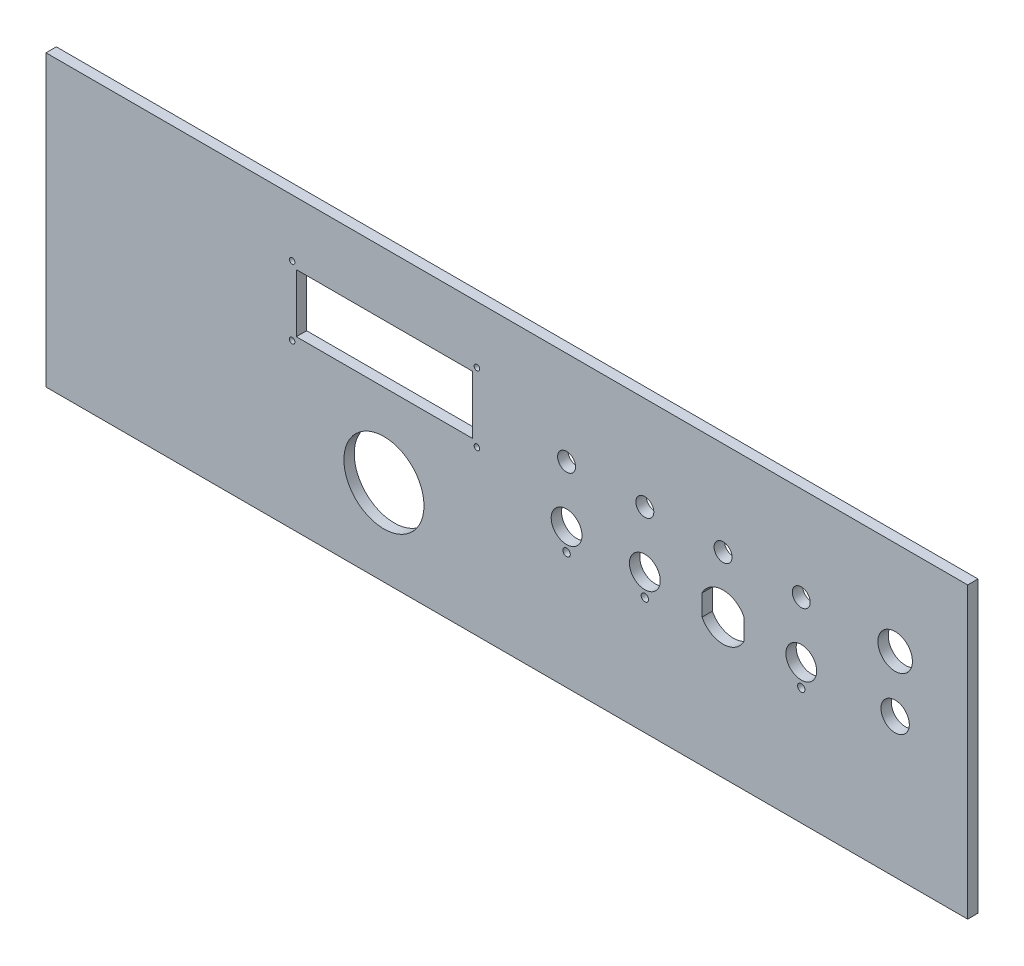
SolidWorks part; units mm, degrees
ref_plane "Front Plane" through (0, 0, 0) normal (0, 0, 1) x (1, 0, 0)
ref_plane "Top Plane" through (0, 0, 0) normal (0, 1, 0) x (1, 0, 0)
ref_plane "Right Plane" through (0, 0, 0) normal (1, 0, 0) x (0, 0, -1)
sketch "Sketch2" plane through (0, 0, 0) normal (0, 0, 1) x (1, 0, 0)
  line L1 (0, 0) -> (374.0912, 0)
  line L2 (0, 0) -> (0, 117.5004)
  line L3 (0, 117.5004) -> (374.0912, 117.5004)
  line L4 (374.0912, 0) -> (374.0912, 117.5004)
  line L5 (101.6, 92.1004) -> (173.2, 92.1004)
  line L6 (101.6, 92.1004) -> (101.6, 68.5004)
  line L7 (101.6, 68.5004) -> (173.2, 68.5004)
  line L8 (173.2, 92.1004) -> (173.2, 68.5004)
  circle A0 centre (137.16, 34.9504) radius 16.25
  dimension "D7" = 32.5
  dimension "D1" = 117.5004
  dimension "D2" = 374.0912
  dimension "D3" = 23.6
  dimension "D4" = 101.6
  dimension "D5" = 25.4
  dimension "D6" = 71.6
  dimension "D8" = 82.55
  dimension "D9" = 137.16
extrude "Boss-Extrude1" add sketch "Sketch2" along normal blind 4.191
sketch "Sketch3" plane through (0, 0, 4.191) normal (0, 0, 1) x (1, 0, 0)
  line L0 (101.6, 92.1004) -> (101.6, 68.5004) construction
  line L1 (173.2, 68.5004) -> (173.2, 92.1004) construction
  line L2 (173.2, 92.1004) -> (101.6, 92.1004) construction
  line L3 (101.6, 68.5004) -> (173.2, 68.5004) construction
  point P0 (99.9, 94.3004)
  point P1 (174.9, 94.3004)
  point P2 (174.9, 66.3004)
  point P3 (99.9, 66.3004)
  dimension "D1" = 1.7
  dimension "D2" = 1.7
  dimension "D3" = 1.7
  dimension "D4" = 1.7
  dimension "D5" = 2.2
  dimension "D6" = 2.2
  dimension "D7" = 2.2
  dimension "D8" = 2.2
hole_wizard "#4-40 Tapped Hole1" positions "Sketch5" profile "Sketch6" tap size "#4-40" standard "ANSI Inch" end condition up to next
sketch "Sketch5" plane through (0, 0, 4.191) normal (0, 0, 1) x (1, 0, 0)
  point P0 (99.9, 94.3004)
  point P3 (174.9, 94.3004)
  point P6 (174.9, 66.3004)
  point P9 (99.9, 66.3004)
sketch "Sketch6" plane through (99.9, 94.3004, 4.191) normal (1, 0, 0) x (0, -1, 0)
  line L0 (0, 0) -> (0, 4.191)
  line L1 (0, 4.191) -> (1.1303, 4.191)
  line L2 (1.1303, 4.191) -> (1.1303, 0)
  line L5 (1.1303, 0) -> (0, 0)
  line L11 (0, -6.35) -> (0, 107.95) construction
  dimension "Thread Major Dia." = 2.2606
  dimension "Thru Tap Drill Depth" = 4.191
sketch "Sketch7" plane through (0, 0, 4.191) normal (0, 0, 1) x (1, 0, 0)
  line L2 (173.2, 68.5004) -> (173.2, 92.1004) construction
  line L3 (374.0912, 117.5004) -> (0, 117.5004) construction
  line L6 (266.291, 52.2883) -> (266.291, 60.7925)
  line L8 (283.309, 52.2883) -> (283.309, 60.7925)
  line L9 (266.291, 52.2883) -> (283.309, 60.7925) construction
  line L10 (266.291, 60.7925) -> (283.309, 52.2883) construction
  circle A0 centre (211.3, 79.4004) radius 3.6449
  circle A1 centre (211.3, 56.5404) radius 6.2484
  circle A2 centre (211.3, 47.5488) radius 1.4986
  circle A3 centre (243.05, 79.4004) radius 3.6449
  circle A4 centre (243.05, 56.5404) radius 6.2484
  circle A5 centre (243.05, 47.5488) radius 1.4986
  circle A6 centre (274.8, 79.4004) radius 3.6449
  arc A7 (266.291, 52.2883) -> (283.309, 52.2883) centre (274.8, 56.5404) ccw
  arc A8 (283.309, 60.7925) -> (266.291, 60.7925) centre (274.8, 56.5404) ccw
  circle A9 centre (306.55, 79.4004) radius 3.6449
  circle A10 centre (306.55, 56.5404) radius 6.2484
  circle A11 centre (306.55, 47.5488) radius 1.4986
  circle A12 centre (344.65, 79.4004) radius 7
  circle A13 centre (344.65, 56.5404) radius 5.7531
  dimension "D1" = 7.2898
  dimension "D2" = 38.1
  dimension "D3" = 38.1
  dimension "D4" = 22.86
  dimension "D5" = 31.75
  dimension "D6" = 2.9972
  dimension "D9" = 7.2898
  dimension "D12" = 12.4968
  dimension "D15" = 2.9972
  dimension "D17" = 12.4968
  dimension "D8" = 7.2898
  dimension "D10" = 19.0246
  dimension "D14" = 7.2898
  dimension "D18" = 12.4968
  dimension "D19" = 2.9972
  dimension "D20" = 14
  dimension "D21" = 11.5062
  dimension "D7" = 8.9916
  dimension "D11" = 31.75
  dimension "D13" = 17.018
  dimension "D16" = 31.75
  dimension "D22" = 38.1
extrude "Cut-Extrude1" cut sketch "Sketch7" against normal through all
